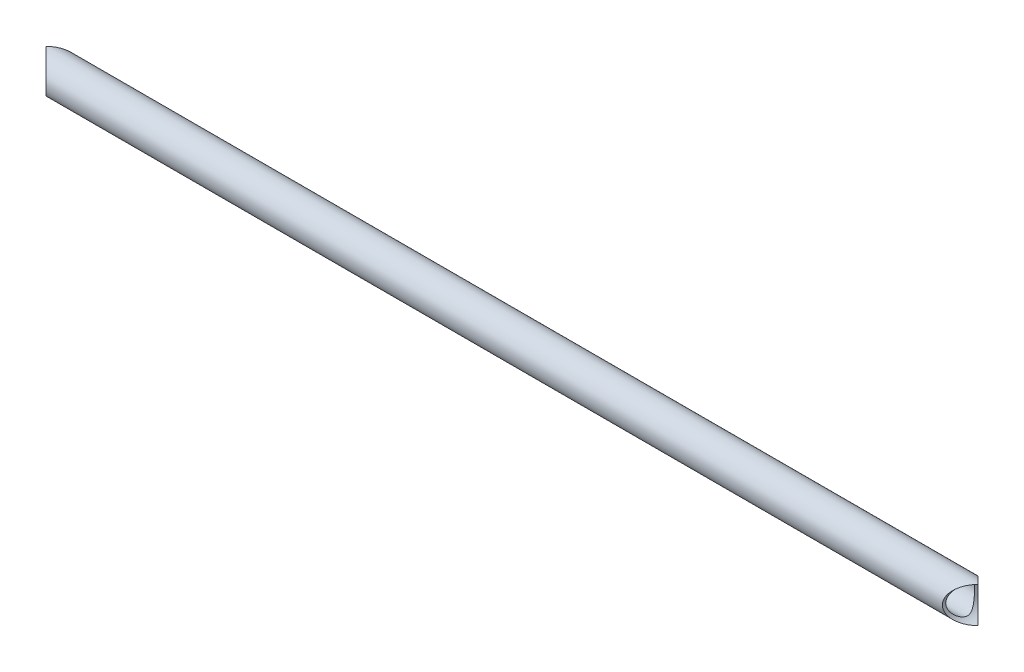
SolidWorks part; units mm, degrees
material "Aço inoxidável forjado"
ref_plane "Plano frontal" through (0, 0, 0) normal (0, 0, 1) x (1, 0, 0)
ref_plane "Plano superior" through (0, 0, 0) normal (0, 1, 0) x (1, 0, 0)
ref_plane "Plano direito" through (0, 0, 0) normal (1, 0, 0) x (0, 0, -1)
ref_plane "Plano1" through (0, 250, 0) normal (0, 1, 0) x (1, 0, 0)
sketch "Esboço1" plane through (0, 0, 0) normal (0, 1, 0) x (1, 0, 0)
  line L0 (0, 162.7552) -> (0, -162.7552)
  line L1 (0, 0) -> (910, 0) construction
  line L2 (910, 265) -> (910, -265) construction
  line L3 (37.1501, 202.6536) -> (910, 265)
  line L4 (37.1501, -202.6536) -> (910, -265)
  arc A0 (0, -162.7552) -> (37.1501, -202.6536) centre (40, -162.7552) ccw
  arc A1 (0, 162.7552) -> (37.1501, 202.6536) centre (40, 162.7552) cw
  point P9 (0, -200)
  point P12 (0, 200)
  dimension "D3" = 40
  dimension "D1" = 400
  dimension "D2" = 910
  dimension "D4" = 530
sketch "Esboço2" plane through (0, 250, 0) normal (0, 1, 0) x (1, 0, 0)
  line L0 (0, 162.7552) -> (0, -162.7552) construction
  line L1 (0, 0) -> (910, 0) construction
  line L2 (910, 265) -> (910, -265) construction
  line L3 (37.1501, 202.6536) -> (910, 265) construction
  line L4 (37.1501, -202.6536) -> (910, -265) construction
  arc A0 (0, -162.7552) -> (37.1501, -202.6536) centre (40, -162.7552) ccw construction
  arc A1 (0, 162.7552) -> (37.1501, 202.6536) centre (40, 162.7552) cw construction
  point P9 (0, -200)
  point P12 (0, 200)
  dimension "D3" = 40
  dimension "D1" = 400
  dimension "D2" = 910
  dimension "D4" = 530
sketch3d "3DSketch1"
  line L0 (37.1501, 0, 202.6536) -> (910, 0, 265) construction
  line L1 (58.5316, 250, 185.1239) -> (58.5316, 250, 204.1808) construction
  line L2 (58.5316, 250, -185.0557) -> (58.5316, 250, -204.1808) construction
  line L3 (0, 250, 0) -> (910, 250, 0) construction
  line L4 (58.5316, 250, -184.1808) -> (58.5316, 250, 184.1808)
  line L7 (58.5316, 250, 185.1239) -> (58.5316, 250, -185.0557) construction
  line L8 (58.5316, 230, 204.1808) -> (58.5316, 0, 204.1808)
  line L11 (58.5316, 230, -204.1808) -> (58.5316, 0, -204.1808)
  line L12 (0, 250, -162.7552) -> (0, 250, 162.7552) construction
  line L14 (37.1501, 0, -202.6536) -> (910, 0, -265) construction
  arc A0 (58.5316, 230, -204.1808) -> (58.5316, 250, -184.1808) centre (58.5316, 230, -184.1808) ccw
  arc A1 (58.5316, 230, 204.1808) -> (58.5316, 250, 184.1808) centre (58.5316, 230, 184.1808) ccw
  circle A2 centre (58.5316, 250, 0) radius 7.9375
  point P5 (58.5316, 250, -204.1808)
  point P7 (78.5316, 230, -184.1808)
  point P11 (58.5316, 250, 204.1808)
  point P13 (38.5316, 230, 184.1808)
  point P15 (58.5316, 250, 7.9375)
  point P17 (37.1501, 0, -202.6536)
  point P18 (87.0231, 0, -206.2159)
  point P34 (196.7435, 15.88, -214.0531)
  dimension "D2" = 20
  dimension "D3" = 15.875
  dimension "D13" = 58.5316
sketch "Esboço4" plane through (0, 250, 0) normal (0, 1, 0) x (1, 0, 0)
  line L0 (60.0173, 204.287) -> (60.0173, -204.287) construction
  line L1 (37.1501, 202.6536) -> (910, 265) construction
  line L2 (0, 200) -> (0, -200) construction
  line L3 (0, -200) -> (910, -265) construction
  line L4 (0, 0) -> (910, 0) construction
  line L5 (910, -265) -> (910, 265) construction
  line L6 (910, 265) -> (0, 200) construction
  point P3 (60.0173, 0)
sketch "Esboço6" plane through (0, 0, 0) normal (0, 0, 1) x (1, 0, 0)
  circle A0 centre (0, 0) radius 7.9375
sketch3d "3DSketch2"
  line L0 (473.5751, 0, 233.8268) -> (473.5751, 230, 233.8268)
  line L1 (37.1501, 0, 202.6536) -> (910, 0, 265) construction
  line L2 (37.1501, 250, 202.6536) -> (910, 250, 265) construction
  line L3 (473.5751, 250, 213.8268) -> (473.5751, 250, -213.8268)
  line L4 (37.1501, 250, -202.6536) -> (910, 250, -265) construction
  line L5 (473.5751, 230, -233.8268) -> (473.5751, 0, -233.8268)
  line L6 (37.1501, 0, -202.6536) -> (910, 0, -265) construction
  arc A0 (473.5751, 250, -213.8268) -> (473.5751, 230, -233.8268) centre (473.5751, 230, -213.8268) ccw
  arc A1 (473.5751, 230, 233.8268) -> (473.5751, 250, 213.8268) centre (473.5751, 230, 213.8268) ccw
  point P14 (473.5751, 250, -233.8268)
  point P15 (453.5751, 230, -213.8268)
  point P18 (473.5751, 250, 233.8268)
  point P19 (453.5751, 230, 213.8268)
  dimension "D1" = 20
sketch "Esboço7" plane through (0, 250, 0) normal (0, 1, 0) x (1, 0, 0)
  line L0 (58.5316, -150) -> (473.5751, -150)
  line L1 (58.5316, 184.1808) -> (58.5316, -184.1808) construction
  line L2 (473.5751, -213.8268) -> (473.5751, 213.8268) construction
  line L3 (0, 0) -> (910, 0) construction
  dimension "D1" = 150
other "Pipe - configured 21.3 X 2.3(1)"
ref_plane "Plano2" through (58.5316, 250, 150) normal (1, 0, 0) x (0, 0, -1)
sketch "Sketch1" plane through (58.5316, 250, 150) normal (1, 0, 0) x (0, 0, -1)
  circle A0 centre (0, 0) radius 6.4375
  circle A1 centre (0, 0) radius 7.9375
  point P3 (0, 0)
  dimension "Out_dia" = 15.875
  dimension "D1" = 1.5
sketch "Esboço9" plane through (0, 0, 0) normal (0, 0, 1) x (1, 0, 0)
  line L0 (473.5751, 257.9375) -> (58.5316, 257.9375) construction
  circle A0 centre (473.5751, 250) radius 7.9375
  circle A1 centre (58.5316, 250) radius 7.9375
extrude "Corte-extrusão1" cut sketch "Esboço9" against normal through all both and the other way through all
